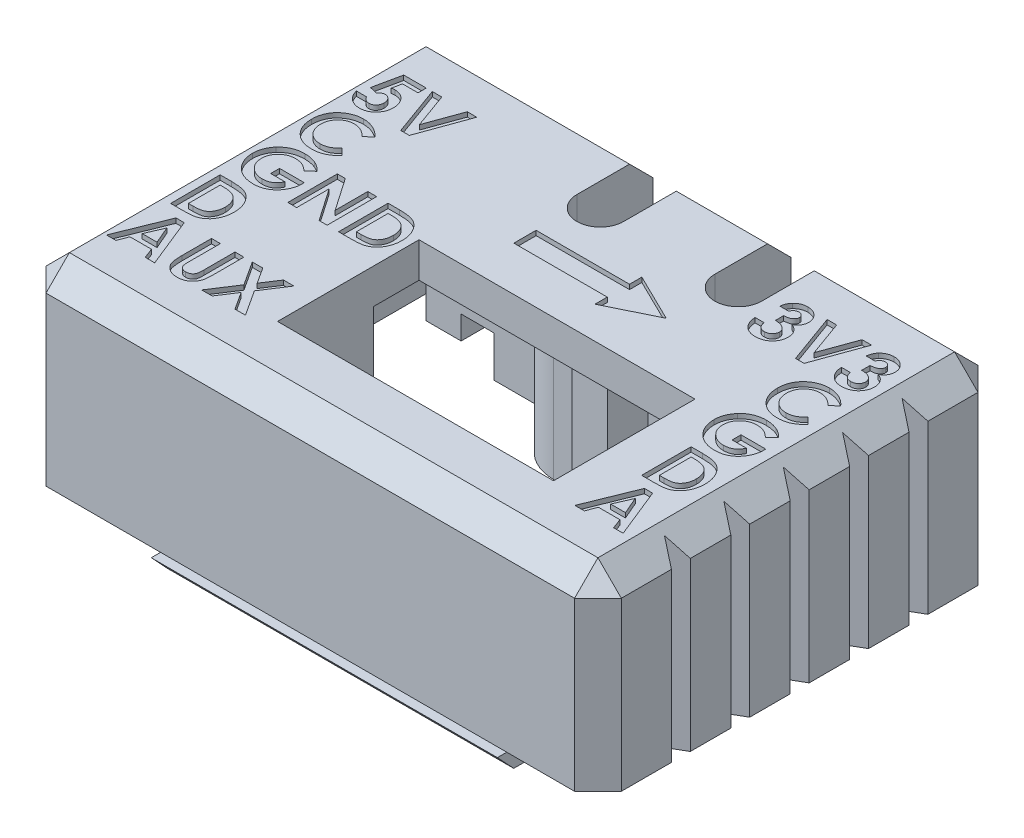
SolidWorks part; units mm, degrees
ref_plane "Front Plane" through (0, 0, 0) normal (0, 0, 1) x (1, 0, 0)
ref_plane "Top Plane" through (0, 0, 0) normal (0, 1, 0) x (1, 0, 0)
ref_plane "Right Plane" through (0, 0, 0) normal (1, 0, 0) x (0, 0, -1)
sketch "Sketch1" plane through (0, 0, 0) normal (0, 1, 0) x (1, 0, 0)
  line L0 (-12.3, -8.625) -> (-12.3, 8.625)
  line L1 (10.3, -6.625) -> (-10.3, -6.625)
  line L2 (10.3, -6.625) -> (10.3, 6.625)
  line L3 (10.3, 6.625) -> (-10.3, 6.625)
  line L4 (-10.3, -6.625) -> (-10.3, 6.625)
  line L5 (10.3, -6.625) -> (-10.3, 6.625) construction
  line L6 (10.3, 6.625) -> (-10.3, -6.625) construction
  line L11 (12.3, 8.625) -> (-12.3, 8.625)
  line L12 (12.3, -8.625) -> (12.3, 8.625)
  line L13 (12.3, -8.625) -> (-12.3, -8.625)
  point P0 (0, 0)
  dimension "D2" = 20.6
  dimension "D3" = 13.25
  dimension "D1" = 2
extrude "Boss-Extrude1" add sketch "Sketch1" along normal blind 8.15
sketch "Sketch2" plane through (0, 8.15, 0) normal (0, -1, 0) x (1, 0, 0)
  line L0 (10.3, 6.625) -> (10.3, -6.625) construction
  line L1 (-10.3, 6.625) -> (10.3, 6.625) construction
  line L2 (10.3, 6.625) -> (10.3, -6.625)
  line L3 (-10.3, 6.625) -> (10.3, 6.625)
  line L4 (10.3, -6.625) -> (-10.3, -6.625) construction
  line L5 (-10.3, -6.625) -> (-10.3, 6.625) construction
  line L6 (10.3, -6.625) -> (-10.3, -6.625)
  line L7 (-10.3, -6.625) -> (-10.3, 6.625)
extrude "Boss-Extrude2" add sketch "Sketch2" along normal blind 1.5
sketch "Sketch3" plane through (0, 8.15, 0) normal (0, 1, 0) x (1, 0, 0)
  line L0 (12.3, 8.625) -> (-12.3, 8.625) construction
  line L1 (-12.3, 8.625) -> (-12.3, -8.625) construction
  circle A0 centre (-1.6, 5.375) radius 1
  circle A1 centre (4.3, 5.375) radius 1
  dimension "D1" = 2
  dimension "D2" = 3.25
  dimension "D3" = 10.7
  dimension "D4" = 16.6
extrude "Cut-Extrude1" cut sketch "Sketch3" against normal through all
sketch "Sketch4" plane through (0, 6.65, 0) normal (0, -1, 0) x (1, 0, 0)
  line L0 (-1.6, -3.375) -> (4.3, -3.375)
  line L1 (6.3, -5.375) -> (6.3, -6.625)
  line L2 (10.3, -6.625) -> (-10.3, -6.625) construction
  line L3 (-3.6, -5.375) -> (-3.6, -6.625)
  line L4 (-3.6, -6.625) -> (6.3, -6.625)
  arc A0 (-1.6, -3.375) -> (-3.6, -5.375) centre (-1.6, -5.375) ccw
  arc A1 (6.3, -5.375) -> (4.3, -3.375) centre (4.3, -5.375) ccw
  circle A2 centre (-1.6, -5.375) radius 1 construction
  circle A3 centre (-1.6, -5.375) radius 1
  circle A4 centre (4.3, -5.375) radius 1 construction
  circle A5 centre (4.3, -5.375) radius 1
  dimension "D1" = 4
extrude "Boss-Extrude3" add sketch "Sketch4" along normal up to surface (6.65 mm away) up to face at (0, 0, 0)
sketch "Sketch5" plane through (0, 0, 0) normal (0, -1, 0) x (1, 0, 0)
  line L1 (-10.3, 6.625) -> (-8.8, 6.625)
  line L2 (-10.3, 6.625) -> (-10.3, 7.625)
  line L3 (-10.3, 7.625) -> (-8.8, 7.625)
  line L4 (-8.8, 6.625) -> (-8.8, 7.625)
  line L5 (10.3, 6.625) -> (8.8, 6.625)
  line L6 (10.3, 6.625) -> (10.3, 7.625)
  line L7 (10.3, 7.625) -> (8.8, 7.625)
  line L8 (8.8, 6.625) -> (8.8, 7.625)
  line L9 (10.3, -6.625) -> (8.8, -6.625)
  line L10 (10.3, -6.625) -> (10.3, -7.625)
  line L11 (10.3, -7.625) -> (8.8, -7.625)
  line L12 (8.8, -6.625) -> (8.8, -7.625)
  line L13 (-10.3, -6.625) -> (-8.8, -6.625)
  line L14 (-10.3, -6.625) -> (-10.3, -7.625)
  line L15 (-10.3, -7.625) -> (-8.8, -7.625)
  line L16 (-8.8, -6.625) -> (-8.8, -7.625)
  dimension "D1" = 1
  dimension "D2" = 1.5
extrude "Boss-Extrude4" add sketch "Sketch5" along normal blind 1
sketch "Sketch6" plane through (0, 0, 0) normal (1, 0, 0) x (0, 0, -1)
  line L0 (-6.625, 0) -> (-6.625, -1.75)
  line L1 (-6.625, -1.75) -> (-7.325, -1.75)
  line L2 (-7.325, -1.75) -> (-8.025, -1)
  line L3 (-8.025, -1) -> (-7.325, -1)
  line L7 (-7.325, 0) -> (-6.625, 0)
  line L8 (-8.625, 0) -> (8.625, 0) construction
  line L9 (-7.325, -1) -> (-7.325, 0)
  line L10 (0, 0) -> (0, -1.5179) construction
  line L11 (7.325, -1) -> (7.325, 0)
  line L12 (7.325, 0) -> (6.625, 0)
  line L13 (8.025, -1) -> (7.325, -1)
  line L14 (7.325, -1.75) -> (8.025, -1)
  line L15 (6.625, -1.75) -> (7.325, -1.75)
  line L16 (6.625, 0) -> (6.625, -1.75)
  line L17 (-6.625, -1) -> (-7.625, -1) construction
  dimension "D1" = 0.7
  dimension "D2" = 1.75
  dimension "D3" = 0.7
extrude "Boss-Extrude5" add sketch "Sketch6" along normal mid plane 14.8
sketch "Sketch7" plane through (0, -1.75, 0) normal (0, -1, 0) x (1, 0, 0)
  line L0 (7.4, 6.625) -> (7.4, 7.325) construction
  line L1 (-7.4, 6.625) -> (7.4, 6.625)
  line L2 (-7.4, 6.625) -> (-7.4, 5.725)
  line L3 (-7.4, 5.725) -> (7.4, 5.725)
  line L4 (7.4, 6.625) -> (7.4, 5.725)
  dimension "D1" = 0.9
extrude "Boss-Extrude6" add sketch "Sketch7" against normal up to surface (8.4 mm away) up to face at (0.81, 6.65, -2.9922)
sketch "Sketch8" plane through (0, 6.65, 0) normal (0, -1, 0) x (1, 0, 0)
  line L0 (-10.3, -6.625) -> (-3.6, -6.625) construction
  line L1 (0.95, -1.625) -> (2.45, -1.625)
  line L2 (0.95, -1.625) -> (0.95, -6.625)
  line L3 (0.95, -6.625) -> (2.45, -6.625)
  line L4 (2.45, -1.625) -> (2.45, -6.625)
  line L5 (-12.3, -8.625) -> (-12.3, 8.625) construction
  point P8 (1.7, -1.625)
  dimension "D1" = 1.5
  dimension "D2" = 14
  dimension "D3" = 5
extrude "Boss-Extrude7" add sketch "Sketch8" along normal offset from surface (8.15 mm away) 1.5 up to face at (0, 0, 0) offset beyond the face yes
sketch "Sketch9" plane through (0, 0, 0) normal (0, -1, 0) x (1, 0, 0)
  line L0 (-3.6, -6.625) -> (6.3, -6.625)
  line L1 (-3.6, -5.375) -> (-3.6, -6.625) construction
  line L2 (-3.6, -5.375) -> (-3.6, -6.625)
  line L3 (6.3, -6.625) -> (6.3, -5.375) construction
  line L4 (6.3, -6.625) -> (6.3, -5.375)
  line L5 (-1.6, -3.375) -> (4.3, -3.375)
  arc A0 (-1.6, -3.375) -> (-3.6, -5.375) centre (-1.6, -5.375) ccw construction
  arc A1 (-1.6, -3.375) -> (-3.6, -5.375) centre (-1.6, -5.375) ccw
  arc A2 (6.3, -5.375) -> (4.3, -3.375) centre (4.3, -5.375) ccw construction
  arc A3 (6.3, -5.375) -> (4.3, -3.375) centre (4.3, -5.375) ccw
  circle A5 centre (-1.6, -5.375) radius 1 construction
  circle A7 centre (-1.6, -5.375) radius 1
  circle A8 centre (4.3, -5.375) radius 1 construction
  circle A9 centre (4.3, -5.375) radius 1
extrude "Boss-Extrude8" add sketch "Sketch9" along normal offset from surface (0.9 mm away) 0.6 up to face at (1.7, -1.5, -4.125)
sketch "Sketch11" plane through (0, 6.65, 0) normal (0, -1, 0) x (1, 0, 0)
  line L0 (-12.3, -8.625) -> (-12.3, 8.625) construction
  line L1 (-10.3, 6.625) -> (-4.3, 6.625)
  line L2 (-10.3, 6.625) -> (-10.3, 1.625)
  line L3 (-10.3, 1.625) -> (-4.3, 1.625)
  line L4 (-4.3, 6.625) -> (-4.3, 1.625)
  line L5 (10.3, 6.625) -> (7.5, 6.625)
  line L6 (10.3, 6.625) -> (10.3, 1.625)
  line L7 (10.3, 1.625) -> (7.5, 1.625)
  line L8 (7.5, 6.625) -> (7.5, 1.625)
  line L10 (12.3, 8.625) -> (12.3, -8.625) construction
  dimension "D1" = 5
  dimension "D2" = 4.8
  dimension "D3" = 8
extrude "Boss-Extrude9" add sketch "Sketch11" along normal up to surface (6.65 mm away) up to face at (0, 0, 0)
sketch "Sketch16" plane through (0, 6.65, 0) normal (0, -1, 0) x (1, 0, 0)
  line L0 (-4.3, 1.625) -> (-4.3, 5.725) construction
  line L1 (-4.3, 5.725) -> (7.5, 5.725)
  line L2 (-4.3, 5.725) -> (-4.3, -0.325)
  line L3 (-4.3, -0.325) -> (7.5, -0.325)
  line L4 (7.5, 5.725) -> (7.5, -0.325)
  line L5 (-12.3, 8.625) -> (12.3, 8.625) construction
  line L6 (7.5, 6.625) -> (7.5, 1.625) construction
  dimension "D1" = 2.9
  dimension "D2" = 6.05
extrude "Cut-Extrude6" cut sketch "Sketch16" against normal through all both
sketch "Sketch10" plane through (0, 8.15, 0) normal (0, 1, 0) x (1, 0, 0)
  line L0 (-11.2, 3.98) -> (11, 3.98) construction
  line L3 (-11.2, -6.18) -> (11, -6.18) construction
  line L4 (-11.2, -3.64) -> (11, -3.64) construction
  line L5 (-11.2, -1.1) -> (11, -1.1) construction
  line L6 (-11.2, 1.44) -> (11, 1.44) construction
  line L7 (-12.3, 8.625) -> (-12.3, -8.625) construction
  line L8 (12.3, -8.625) -> (12.3, 8.625) construction
  line L17 (1.3663, -5.4758) -> (1.3663, 0) construction
  line L23 (1.8468, 2.2265) -> (1.8468, 1.6996)
  line L24 (1.8468, 2.2265) -> (-2.1474, 2.2265)
  line L25 (1.8468, 3.1778) -> (-2.1474, 3.1778)
  line L26 (-2.1474, 2.2265) -> (-2.1474, 3.1778)
  line L27 (1.8468, 1.6996) -> (3.891, 2.7021)
  line L28 (3.891, 2.7021) -> (1.8468, 3.7047)
  line L29 (1.8468, 3.7047) -> (1.8468, 3.1778)
  text T0 "5V" font "Century Gothic" height in points 8
  text T1 "C" font "Century Gothic" height in points 8
  text T2 "GND" font "Century Gothic" height in points 8
  text T3 "D" font "Century Gothic" height in points 8
  text T4 "AUX" font "Century Gothic" height in points 8
  text T5 "3V3\r\n" font "Century Gothic" height in points 8
  text T6 "C" font "Century Gothic" height in points 8
  text T7 "G\r\n" font "Century Gothic" height in points 8
  text T8 "D" font "Century Gothic" height in points 8
  text T9 "A\r\n" font "Century Gothic" height in points 8
  point P4 (2.0509, 3.6584)
  point P14 (1.8468, 3.7047)
  point P23 (-0.1, -3.64)
  point P37 (0.0204, -3.8716)
  dimension "D1" = 2.54
  dimension "D2" = 2.54
  dimension "D3" = 2.54
  dimension "D4" = 2.54
  dimension "D5" = 1.1
  dimension "D6" = 1.1
  dimension "D7" = 1.3
extrude "Cut-Extrude2" cut sketch "Sketch10" against normal blind 0.2
sketch "Sketch12" plane through (0, 0, -8.625) normal (0, 0, -1) x (-1, 0, 0)
  line L0 (0.6, -0.9) -> (2.6, -0.9) construction
  line L1 (-5.3, -0.9) -> (-3.3, -0.9) construction
  line L2 (0.6, -0.9) -> (2.6, -0.9) construction
  line L3 (-5.3, -0.9) -> (-3.3, -0.9) construction
  line L4 (-5.3, 3.15) -> (-5.3, 8.15)
  line L5 (-12.3, 8.15) -> (12.3, 8.15) construction
  line L6 (-5.3, 8.15) -> (-3.3, 8.15)
  line L7 (-3.3, 8.15) -> (-3.3, 3.15)
  line L8 (-3.3, 3.15) -> (-5.3, 3.15)
  line L9 (0.6, 3.15) -> (0.6, 8.15)
  line L10 (0.6, 8.15) -> (2.6, 8.15)
  line L11 (2.6, 8.15) -> (2.6, 3.15)
  line L12 (2.6, 3.15) -> (0.6, 3.15)
  dimension "D1" = 5
extrude "Cut-Extrude3" cut sketch "Sketch12" against normal blind 3.25
chamfer "Chamfer1" distance 1 angle 45 10 edges at (1.35, 8.15, -8.625) (-7.45, 8.15, -8.625) (-12.3, 8.15, 0) (-12.3, 4.075, 8.625) (0, 8.15, 8.625) (12.3, 4.075, 8.625) (12.3, 4.075, -8.625) (8.8, 8.15, -8.625) (12.3, 8.15, 0) (-12.3, 4.075, -8.625)
sketch "Sketch13" plane through (-12.3, 0, 0) normal (-1, 0, 0) x (0, 0, 1)
  line L1 (0.5, -12.3045) -> (-0.5, -12.3045)
  line L2 (0.5, -12.3045) -> (0.5, 12.3045)
  line L3 (0.5, 12.3045) -> (-0.5, 12.3045)
  line L4 (-0.5, -12.3045) -> (-0.5, 12.3045)
  line L5 (0.5, -12.3045) -> (-0.5, 12.3045) construction
  line L6 (0.5, 12.3045) -> (-0.5, -12.3045) construction
  point P0 (0, 0)
  dimension "D1" = 1
extrude "Cut-Extrude4" cut sketch "Sketch13" against normal blind 0.3
sketch "Sketch15" plane through (0, 8.15, 0) normal (0, 1, 0) x (1, 0, 0)
  line L0 (11.6, 0) -> (12.466, -0.5)
  line L1 (12.466, -0.5) -> (12.466, 0.5)
  line L2 (12.466, 0.5) -> (11.6, 0)
  line L3 (12.3, 7.625) -> (12.3, -7.625) construction
  dimension "D1" = 1
  dimension "D2" = 0.7
extrude "Cut-Extrude5" cut sketch "Sketch15" against normal through all both and the other way through all
pattern_linear "LPattern1" count 3 spacing 2.54 along (0, 0, 1) of "Cut-Extrude4", "Cut-Extrude5"
pattern_linear "LPattern2" count 3 spacing 2.54 along (0, 0, -1) of "Cut-Extrude4", "Cut-Extrude5"
